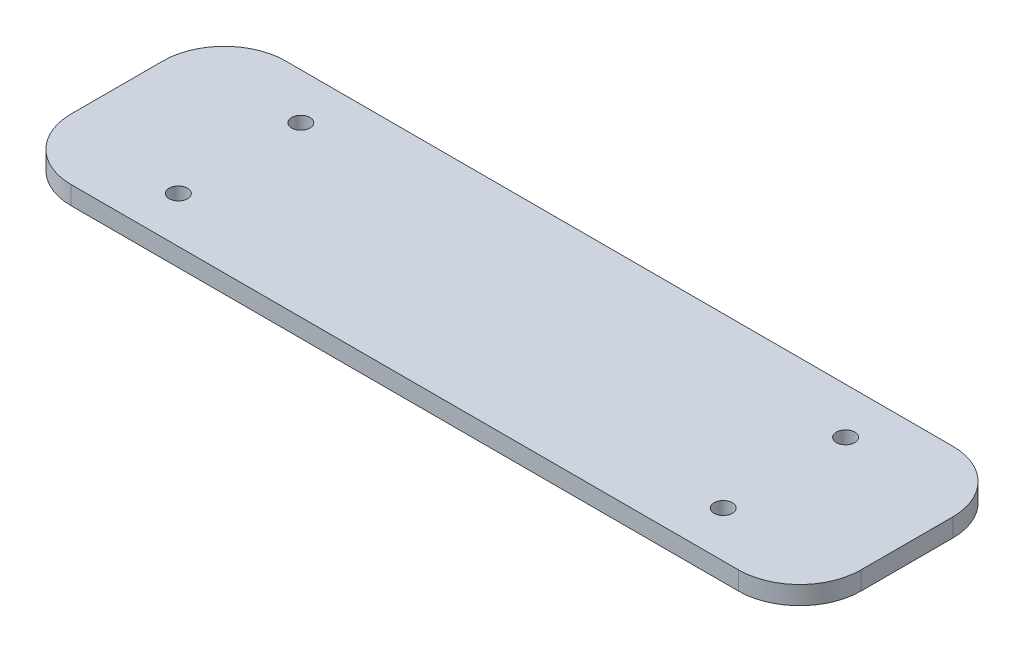
SolidWorks part; units mm, degrees
ref_plane "前基準面" through (0, 0, 0) normal (0, 0, 1) x (1, 0, 0)
ref_plane "上基準面" through (0, 0, 0) normal (0, 1, 0) x (1, 0, 0)
ref_plane "右基準面" through (0, 0, 0) normal (1, 0, 0) x (0, 0, -1)
sketch "草圖1" plane through (0, 0, 0) normal (0, 1, 0) x (1, 0, 0)
  line L1 (-64.5, 17.5) -> (64.5, 17.5)
  line L2 (-64.5, 17.5) -> (-64.5, -17.5)
  line L3 (-64.5, -17.5) -> (64.5, -17.5)
  line L4 (64.5, 17.5) -> (64.5, -17.5)
  line L5 (-64.5, 17.5) -> (64.5, -17.5) construction
  line L6 (-64.5, -17.5) -> (64.5, 17.5) construction
  line L7 (-44.5, 10) -> (44.5, 10) construction
  line L8 (-44.5, 10) -> (-44.5, -10) construction
  line L9 (-44.5, -10) -> (44.5, -10) construction
  line L10 (44.5, 10) -> (44.5, -10) construction
  circle A4 centre (-44.5, 10) radius 1.5
  circle A5 centre (-44.5, -10) radius 1.5
  circle A6 centre (44.5, -10) radius 1.5
  circle A7 centre (44.5, 10) radius 1.5
  point P0 (0, 0)
  point P10 (0, 10)
  point P15 (-44.5, 0)
  dimension "D3" = 20
  dimension "D6" = 3
  dimension "D1" = 129
  dimension "D2" = 35
  dimension "D4" = 89
extrude "填料-伸長1" add sketch "草圖1" along normal blind 3
fillet "圓角1" radius 10 4 edges at (-64.5, 1.5, 17.5) (64.5, 1.5, 17.5) (64.5, 1.5, -17.5) (-64.5, 1.5, -17.5)
